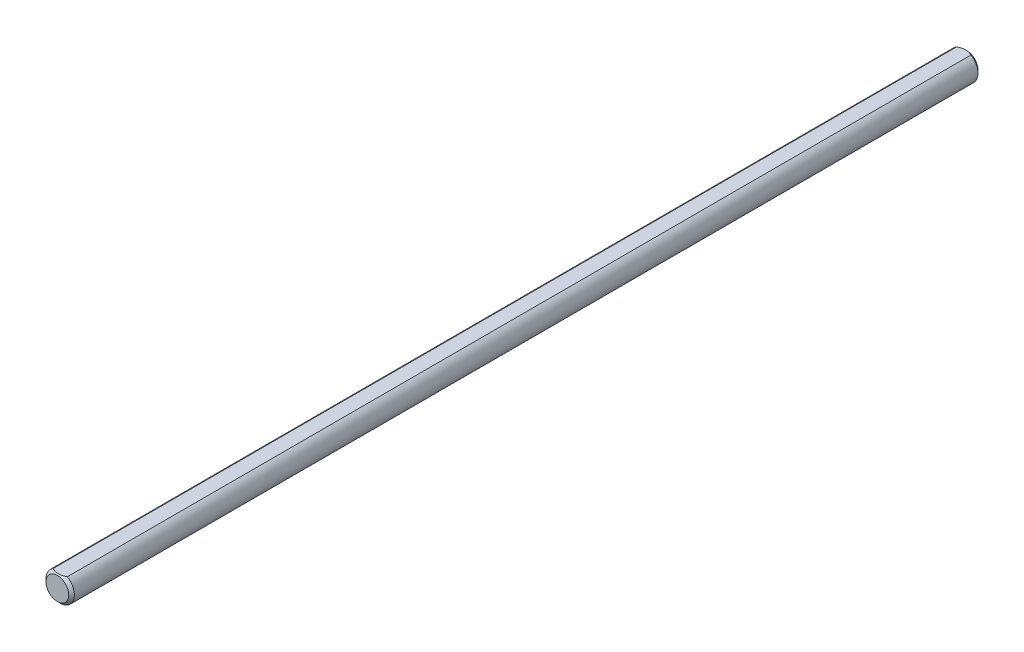
SolidWorks part; units mm, degrees
ref_plane "Front" through (0, 0, 0) normal (0, 0, 1) x (1, 0, 0)
ref_plane "Top" through (0, 0, 0) normal (0, 1, 0) x (1, 0, 0)
ref_plane "Right" through (0, 0, 0) normal (1, 0, 0) x (0, 0, -1)
sketch "Sketch1" plane through (0, 0, 0) normal (0, 0, 1) x (1, 0, 0)
  circle A0 centre (0, 0) radius 3.175
  dimension "D1" = 6.35
extrude "Extrude1" add sketch "Sketch1" along normal mid plane 203.2
chamfer "Chamfer1" distance 0.635 angle 45 2 edges at (3.175, 0, -101.6) (3.175, 0, 101.6)
sketch "Sketch13" plane through (0, 0, 0) normal (0, 0, 1) x (1, 0, 0)
  line L3 (-1.5875, 2.7496) -> (1.5875, 2.7496)
  circle A0 centre (0, 0) radius 3.175 construction
  arc A1 (1.5875, 2.7496) -> (-1.5875, 2.7496) centre (0, 0) ccw
  dimension "D1" = 3.175
extrude "Extrude7" cut sketch "Sketch13" against normal through all and the other way through all
equation "\"D1@Chamfer1\" = \"D1@Sketch1\" * .1"
equation "\"D1@Sketch13\" = \"D1@Sketch1\" * .5"
